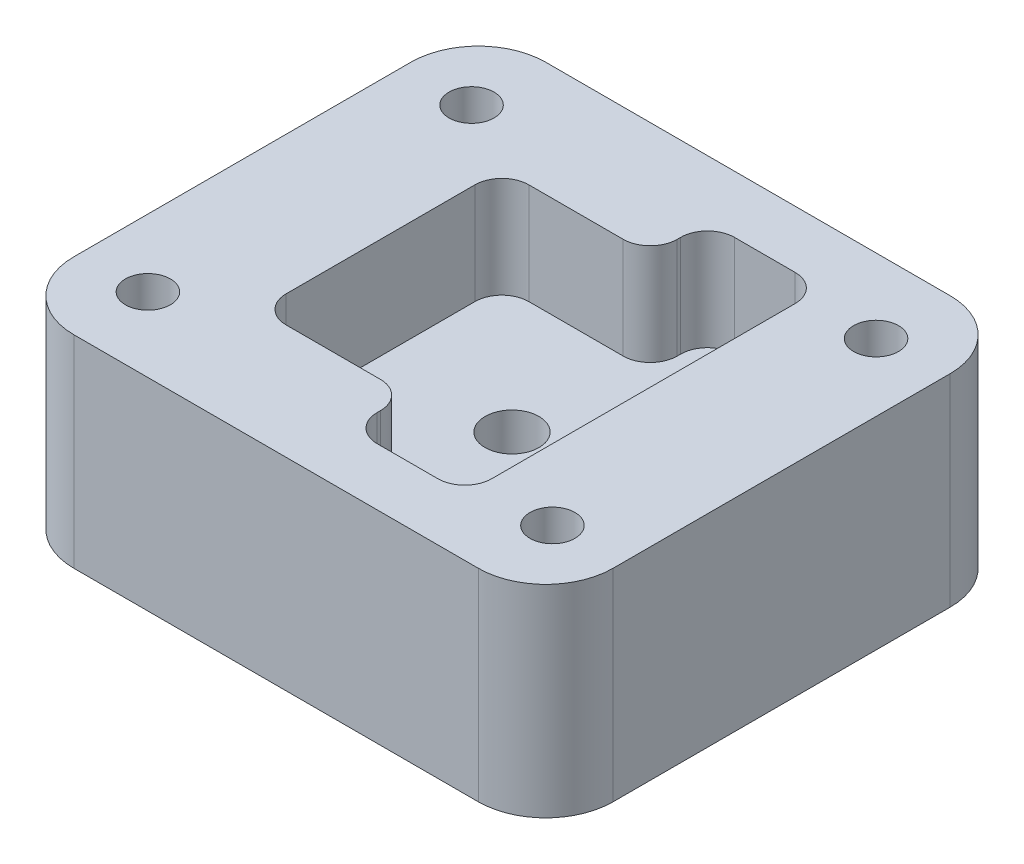
SolidWorks part; units mm, degrees
ref_plane "Front Plane" through (0, 0, 0) normal (0, 0, 1) x (1, 0, 0)
ref_plane "Top Plane" through (0, 0, 0) normal (0, 1, 0) x (1, 0, 0)
ref_plane "Right Plane" through (0, 0, 0) normal (1, 0, 0) x (0, 0, -1)
sketch "Sketch1" plane through (0, 0, 0) normal (0, 1, 0) x (1, 0, 0)
  line L0 (0, 17.5) -> (40, 17.5) construction
  line L1 (0, 0) -> (40, 0)
  line L2 (0, 0) -> (0, 35)
  line L3 (0, 35) -> (40, 35)
  line L4 (40, 0) -> (40, 35)
  circle A0 centre (5, 29.5) radius 1.6667
  circle A1 centre (35, 29.5) radius 1.6667
  circle A2 centre (5, 5.5) radius 1.6667
  circle A3 centre (35, 5.5) radius 1.6667
  dimension "D3" = 3.3333
  dimension "D4" = 3.3333
  dimension "D5" = 3.3333
  dimension "D6" = 3.3333
  dimension "D1" = 35
  dimension "D2" = 40
  dimension "D7" = 30
  dimension "D8" = 5
  dimension "D9" = 30
  dimension "D10" = 5
  dimension "D11" = 24
  dimension "D12" = 12
  dimension "D13" = 12
extrude "Boss-Extrude1" add sketch "Sketch1" along normal blind 15
fillet "Fillet1" radius 5 4 edges at (0, 7.5, 0) (0, 7.5, -35) (40, 7.5, -35) (40, 7.5, 0)
sketch "Sketch4" plane through (0, 15, 0) normal (0, 1, 0) x (1, 0, 0)
  line L23 (29.75, 30.75) -> (21.25, 30.75)
  line L24 (29.75, 4.25) -> (29.75, 30.75)
  line L25 (21.25, 4.25) -> (29.75, 4.25)
  line L26 (10.25, 26.5) -> (10.25, 8.5)
  line L33 (21.25, 8.5) -> (21.25, 4.25)
  line L34 (10.25, 8.5) -> (21.25, 8.5)
  line L35 (21.25, 26.5) -> (10.25, 26.5)
  line L36 (21.25, 26.5) -> (21.25, 30.75)
  line L37 (29.75, 17.5) -> (10.25, 17.5) construction
  line L38 (29.75, 30.75) -> (10.25, 30.75) construction
  line L39 (10.25, 30.75) -> (10.25, 26.5) construction
  line L40 (20, 30.75) -> (20, 4.25) construction
  line L41 (20, 4.25) -> (21.25, 4.25) construction
  line L42 (40, 17.5) -> (0, 17.5) construction
  line L43 (40, 5) -> (40, 30) construction
  line L44 (0, 30) -> (0, 5) construction
  line L45 (20, 35) -> (20, 0) construction
  line L46 (35, 35) -> (5, 35) construction
  line L47 (5, 0) -> (35, 0) construction
  dimension "D1" = 90
  dimension "D2" = 90
  dimension "D3" = 8.5
  dimension "D4" = 26.5
  dimension "D5" = 18
  dimension "D6" = 0
  dimension "D7" = 11
  dimension "D8" = 0
  dimension "D9" = 0
extrude "Cut-Extrude1" cut sketch "Sketch4" against normal blind 7.5
fillet "Fillet2" radius 2 8 edges at (21.25, 11.25, -26.5) (29.75, 11.25, -4.25) (29.75, 11.25, -30.75) (10.25, 11.25, -26.5) (10.25, 11.25, -8.5) (21.25, 11.25, -4.25) (21.25, 11.25, -30.75) (21.25, 11.25, -8.5)
sketch "Sketch5" plane through (0, 7.5, 0) normal (0, 1, 0) x (1, 0, 0)
  line L0 (29.75, 17.5) -> (10.25, 17.5) construction
  line L1 (29.75, 6.25) -> (29.75, 28.75) construction
  line L2 (10.25, 24.5) -> (10.25, 10.5) construction
  line L3 (20, 17.5) -> (20, 8.354) construction
  arc A0 (21.25, 6.5) -> (19.25, 8.5) centre (19.25, 6.5) ccw construction
  circle A1 centre (20, 17.5) radius 2
  dimension "D1" = 4
extrude "Cut-Extrude2" cut sketch "Sketch5" against normal blind 7.5
sketch "Sketch6" plane through (0, 0, 0) normal (0, -1, 0) x (1, 0, 0)
  circle A0 centre (20, -17.5) radius 5
  dimension "D1" = 10
extrude "Cut-Extrude3" cut sketch "Sketch6" against normal blind 2.5
